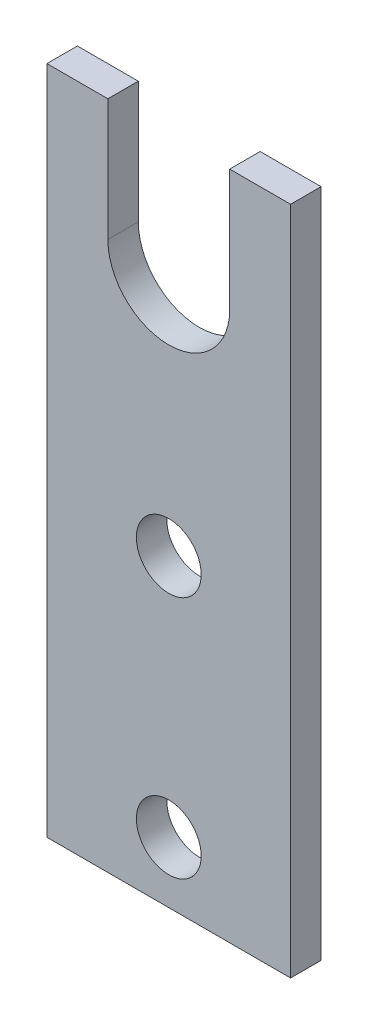
SolidWorks part; units mm, degrees
material "Plain Carbon Steel"
ref_plane "Front" through (0, 0, 0) normal (0, 0, 1) x (1, 0, 0)
ref_plane "Top" through (0, 0, 0) normal (0, 1, 0) x (1, 0, 0)
ref_plane "Right" through (0, 0, 0) normal (1, 0, 0) x (0, 0, -1)
sketch "Sketch1" plane through (0, 0, 0) normal (0, 0, 1) x (1, 0, 0)
  line L1 (-12.7, -34.925) -> (12.7, -34.925)
  line L2 (-12.7, -34.925) -> (-12.7, 34.925)
  line L3 (-12.7, 34.925) -> (12.7, 34.925)
  line L4 (12.7, -34.925) -> (12.7, 34.925)
  line L5 (-12.7, -34.925) -> (12.7, 34.925) construction
  line L6 (-12.7, 34.925) -> (12.7, -34.925) construction
  point P0 (0, 0)
  dimension "D1" = 25.4
  dimension "D2" = 69.85
extrude "Boss-Extrude1" add sketch "Sketch1" along normal blind 3.175
sketch "Sketch2" plane through (0, 0, 3.175) normal (0, 0, 1) x (1, 0, 0)
  line L0 (0, -34.925) -> (0, -28.575) construction
  line L1 (-12.7, -34.925) -> (12.7, -34.925) construction
  line L2 (0, -28.575) -> (0, -3.175) construction
  line L3 (0, -3.175) -> (0, 3.175) construction
  line L4 (-6.35, 34.925) -> (-6.35, 22.225)
  line L5 (12.7, 34.925) -> (-12.7, 34.925) construction
  line L6 (6.35, 22.225) -> (6.35, 34.925)
  line L7 (6.35, 34.925) -> (-6.35, 34.925)
  line L8 (0, 22.225) -> (0, 3.175) construction
  arc A0 (-6.35, 22.225) -> (6.35, 22.225) centre (0, 22.225) ccw
  dimension "D3" = 12.7
  dimension "D1" = 6.35
  dimension "D2" = 38.1
  dimension "D4" = 12.7
extrude "Cut-Extrude1" cut sketch "Sketch2" against normal through all
hole_wizard "1/4 Clearance Hole1" positions "Sketch4" profile "Sketch3" hole size "1/4" standard "ANSI Inch" end condition through all
sketch "Sketch4" plane through (0, 0, 3.175) normal (0, 0, 1) x (1, 0, 0)
  point P3 (0, -28.575)
  point P7 (0, -3.175)
sketch "Sketch3" plane through (0, -28.575, 3.175) normal (1, 0, 0) x (0, -1, 0)
  line L0 (0, 0) -> (0, 3.175)
  line L1 (0, 3.175) -> (3.3782, 3.175)
  line L2 (3.3782, 3.175) -> (3.3782, 0)
  line L5 (3.3782, 0) -> (0, 0)
  line L11 (0, -6.35) -> (0, 107.95) construction
  dimension "Thru Hole Dia." = 6.7564
  dimension "Thru Hole Depth" = 3.175
